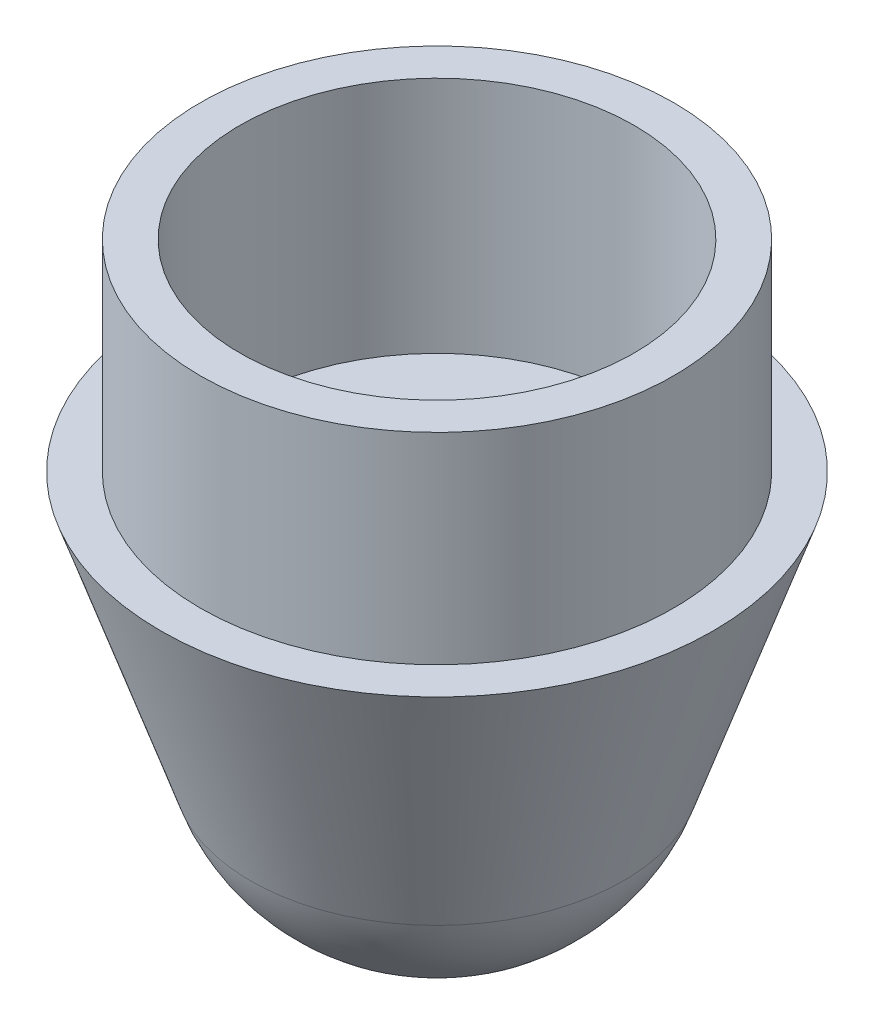
SolidWorks part; units mm, degrees
material "CA"
ref_plane "Plan de face" through (0, 0, 0) normal (0, 0, 1) x (1, 0, 0)
ref_plane "Plan de dessus" through (0, 0, 0) normal (0, 1, 0) x (1, 0, 0)
ref_plane "Plan de droite" through (0, 0, 0) normal (1, 0, 0) x (0, 0, -1)
sketch "Esquisse1" plane through (0, 0, 0) normal (0, 0, 1) x (1, 0, 0)
  line L0 (0, 0) -> (0, 15.9167) construction
  line L1 (-10, 0) -> (-10, 12.0833)
  line L2 (-10, 12.0833) -> (-12, 12.0833)
  line L3 (-12, 12.0833) -> (-12, 1.8807)
  line L4 (-12, 1.8807) -> (-14, 1.8807)
  line L5 (-14, 1.8807) -> (-9.4595, -11.3626)
  line L6 (0, -18.1193) -> (10.8402, -18.1193) construction
  line L7 (0, 0) -> (0, -18.1193)
  line L8 (-10, 0) -> (0, 0)
  arc A0 (-9.4595, -11.3626) -> (0, -18.1193) centre (0, -8.1193) ccw
  dimension "D5" = 10
  dimension "D1" = 2
  dimension "D2" = 20
  dimension "D3" = 2
  dimension "D4" = 20
revolve "Révolution1" add sketch "Esquisse1" angle 360 about L0
